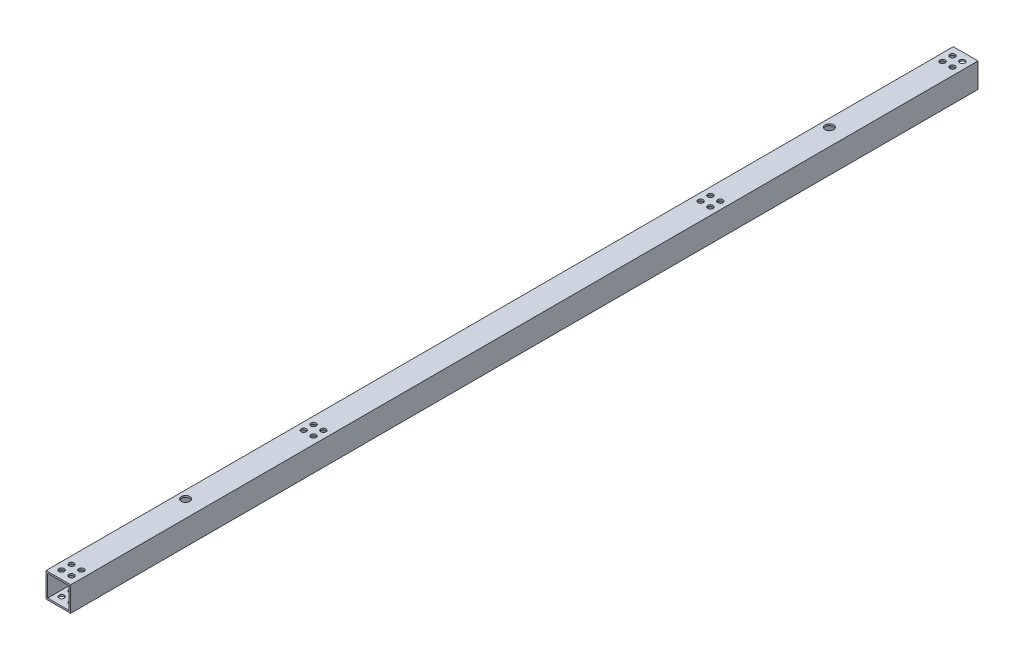
SolidWorks part; units mm, degrees
ref_plane "前视基准面" through (0, 0, 0) normal (0, 0, 1) x (1, 0, 0)
ref_plane "上视基准面" through (0, 0, 0) normal (0, 1, 0) x (1, 0, 0)
ref_plane "右视基准面" through (0, 0, 0) normal (1, 0, 0) x (0, 0, -1)
other "Configuration Table"
sketch "草图1" plane through (0, 0, 0) normal (0, 0, 1) x (1, 0, 0)
  line L1 (0, 0) -> (15, 0)
  line L2 (0, 0) -> (0, -15)
  line L3 (0, -15) -> (15, -15)
  line L4 (15, 0) -> (15, -15)
  dimension "D1" = 15
  dimension "D2" = 15
extrude "拉伸-薄壁1" add sketch "草图1" along normal blind 551 thin
sketch "草图2" plane through (0, 0, 0) normal (0, 1, 0) x (1, 0, 0)
  line L0 (0, -8) -> (15, -8) construction
  line L1 (0, -551) -> (0, 0) construction
  line L2 (15, -551) -> (15, 0) construction
  line L3 (7.5, 0) -> (7.5, -8) construction
  line L4 (15, 0) -> (0, 0) construction
  line L5 (0, -275.5) -> (15, -275.5) construction
  line L6 (7.5, -551) -> (7.5, -543) construction
  line L7 (0, -543) -> (15, -543) construction
  line L8 (0, -155) -> (15, -155) construction
  line L9 (0, -396) -> (15, -396) construction
  circle A0 centre (4.5, -5) radius 1.6
  circle A1 centre (10.5, -5) radius 1.6
  circle A2 centre (10.5, -11) radius 1.6
  circle A3 centre (4.5, -11) radius 1.6
  circle A4 centre (4.5, -540) radius 1.6
  circle A5 centre (10.5, -540) radius 1.6
  circle A6 centre (10.5, -546) radius 1.6
  circle A7 centre (4.5, -546) radius 1.6
  circle A8 centre (4.75, -80) radius 2.6
  circle A9 centre (4.5, -152) radius 1.6
  circle A10 centre (10.5, -152) radius 1.6
  circle A11 centre (10.5, -158) radius 1.6
  circle A12 centre (4.5, -158) radius 1.6
  circle A13 centre (4.75, -471) radius 2.6
  circle A14 centre (4.5, -393) radius 1.6
  circle A15 centre (10.5, -393) radius 1.6
  circle A16 centre (10.5, -399) radius 1.6
  circle A17 centre (4.5, -399) radius 1.6
  dimension "D2" = 3.2
  dimension "D5" = 5.2
  dimension "D8" = 3.2
  dimension "D1" = 8
  dimension "D3" = 3
  dimension "D4" = 3
  dimension "D6" = 4.75
  dimension "D7" = 80
  dimension "D9" = 155
  dimension "D10" = 3
  dimension "D11" = 3
extrude "切除-拉伸1" cut sketch "草图2" against normal through all
